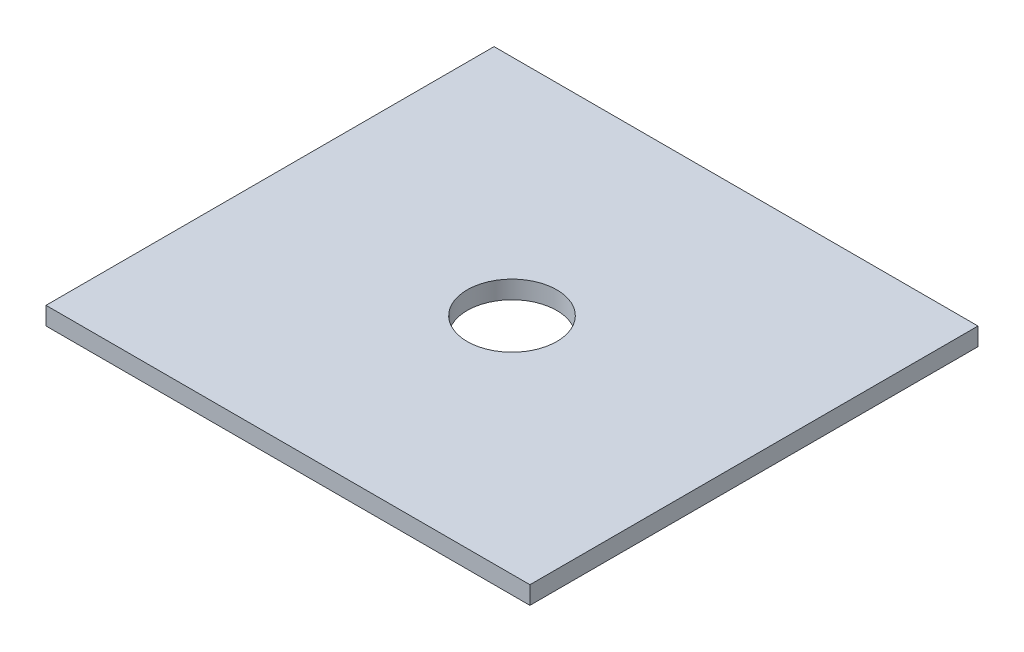
SolidWorks part; units mm, degrees
ref_plane "Front Plane" through (0, 0, 0) normal (0, 0, 1) x (1, 0, 0)
ref_plane "Top Plane" through (0, 0, 0) normal (0, 1, 0) x (1, 0, 0)
ref_plane "Right Plane" through (0, 0, 0) normal (1, 0, 0) x (0, 0, -1)
sketch "Sketch1" plane through (0, 0, 0) normal (0, 1, 0) x (1, 0, 0)
  line L1 (0, 0) -> (54, 0)
  line L2 (0, 0) -> (0, 50)
  line L3 (0, 50) -> (54, 50)
  line L4 (54, 0) -> (54, 50)
  circle A0 centre (27, 25) radius 5
  dimension "D1" = 54
  dimension "D2" = 50
extrude "Boss-Extrude1" add sketch "Sketch1" along normal blind 2
